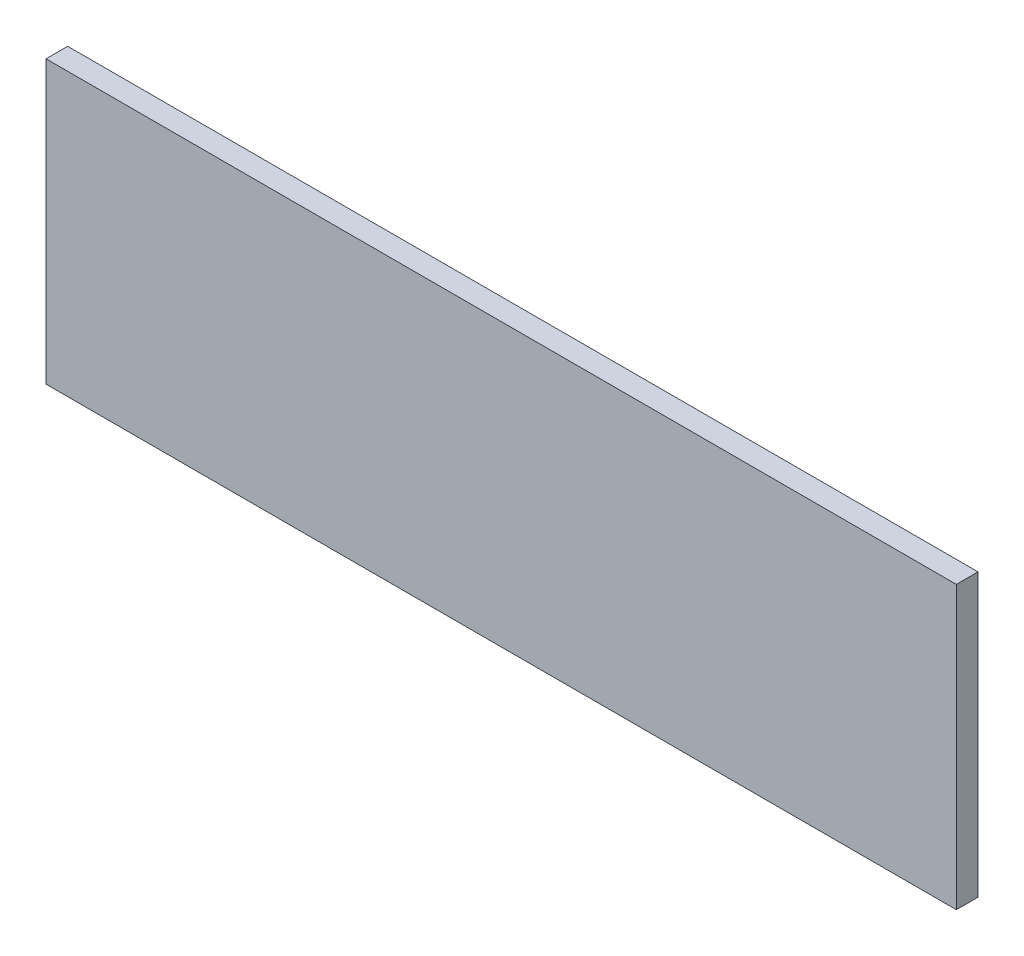
SolidWorks part; units mm, degrees
ref_plane "Front Plane" through (0, 0, 0) normal (0, 0, 1) x (1, 0, 0)
ref_plane "Top Plane" through (0, 0, 0) normal (0, 1, 0) x (1, 0, 0)
ref_plane "Right Plane" through (0, 0, 0) normal (1, 0, 0) x (0, 0, -1)
sketch "Sketch1" plane through (0, 0, 0) normal (0, 0, 1) x (1, 0, 0)
  line L1 (-110, 46.7568) -> (100, 46.7568)
  line L2 (-110, 46.7568) -> (-110, -18.2432)
  line L3 (-110, -18.2432) -> (100, -18.2432)
  line L4 (100, 46.7568) -> (100, -18.2432)
  dimension "D1" = 65
  dimension "D2" = 210
extrude "Boss-Extrude1" add sketch "Sketch1" along normal blind 5
